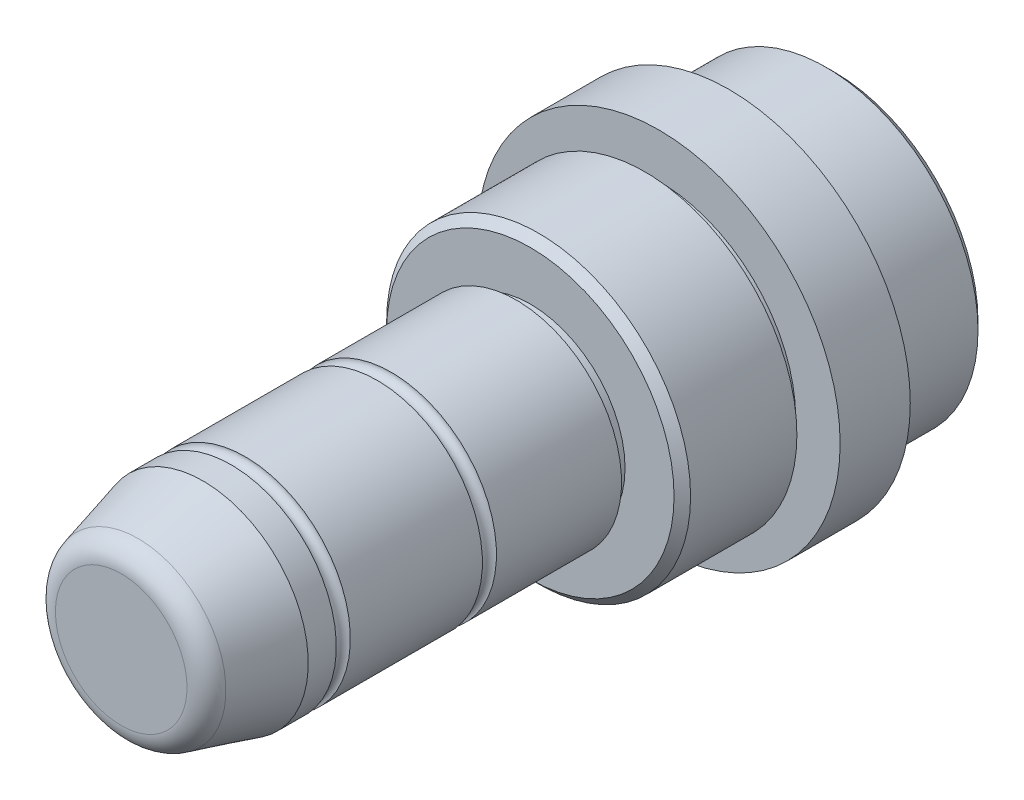
SolidWorks part; units mm, degrees
ref_plane "Спереди" through (0, 0, 0) normal (0, 0, 1) x (1, 0, 0)
ref_plane "Сверху" through (0, 0, 0) normal (0, 1, 0) x (1, 0, 0)
ref_plane "Справа" through (0, 0, 0) normal (1, 0, 0) x (0, 0, -1)
ref_plane "Плоскость4" through (0, 0, 0) normal (0, -1, 0) x (1, 0, 0)
sketch "Эскиз1" plane through (0, 0, 0) normal (0, -1, 0) x (1, 0, 0)
  line L0 (5.6281, 61) -> (0, 61)
  line L1 (0, 61) -> (0, 0)
  line L2 (0, 0) -> (12.2929, 0)
  line L3 (12.2929, 0) -> (13, 0.7071)
  line L4 (13, 0.7071) -> (13, 7.8)
  line L5 (13, 7.8) -> (11.7, 7.8)
  line L6 (11.7, 7.8) -> (11.7, 9)
  line L7 (11.7, 9) -> (15.5, 9)
  line L8 (15.5, 9) -> (15.5, 15)
  line L9 (15.5, 15) -> (11.7, 15)
  line L10 (11.7, 15) -> (11.7, 16.2)
  line L11 (11.7, 16.2) -> (13, 16.2)
  line L12 (13, 16.2) -> (13, 25.2929)
  line L13 (13, 25.2929) -> (12.2929, 26)
  line L14 (12.2929, 26) -> (8.1, 26)
  line L15 (8.1, 26) -> (8.1, 27.2)
  line L16 (8.1, 27.2) -> (9, 27.2)
  line L17 (9, 27.2) -> (9, 37.9)
  line L18 (9, 39.1) -> (9, 50.4)
  line L19 (9, 51.6) -> (9, 54)
  line L20 (9, 54) -> (7.5116, 59.5547)
  line L21 (0, 61.005) -> (0, -0.005) construction
  arc A0 (9, 37.9) -> (9, 39.1) centre (9, 38.5) cw
  arc A1 (9, 50.4) -> (9, 51.6) centre (9, 51) cw
  arc A2 (7.5116, 59.5547) -> (5.6281, 61) centre (5.6281, 59.05) ccw
revolve "Повернуть1" add sketch "Эскиз1" angle 360 about L21
